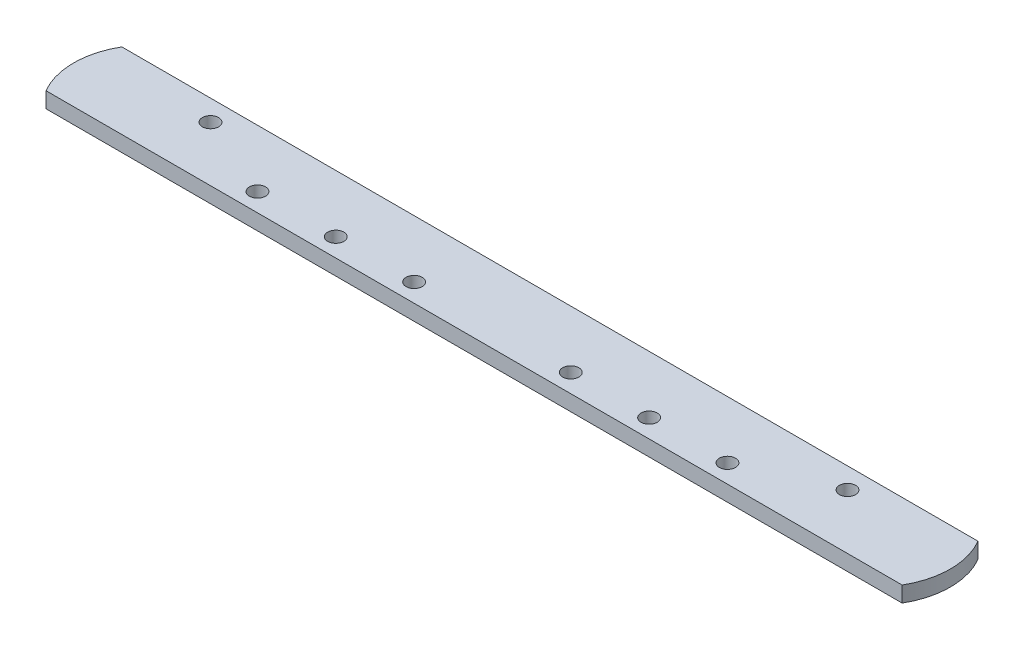
SolidWorks part; units mm, degrees
ref_plane "前视基准面" through (0, 0, 0) normal (0, 0, 1) x (1, 0, 0)
ref_plane "上视基准面" through (0, 0, 0) normal (0, 1, 0) x (1, 0, 0)
ref_plane "右视基准面" through (0, 0, 0) normal (1, 0, 0) x (0, 0, -1)
other "Configuration Table"
sketch "草图2" plane through (0, 0, 0) normal (0, 1, 0) x (1, 0, 0)
  line L0 (-82.2482, 7.3997) -> (81.7125, 7.3997)
  line L1 (-0.2678, 7.3997) -> (-0.2678, -7.1318) construction
  line L2 (81.7125, -7.1318) -> (-82.2482, -7.1318)
  arc A0 (-82.2482, 7.3997) -> (-82.2482, -7.1318) centre (-69.8675, 0.1339) ccw
  arc A1 (81.7125, 7.3997) -> (81.7125, -7.1318) centre (69.3318, 0.1339) cw
  circle A2 centre (-61.2775, 3.3997) radius 1.55
  circle A3 centre (-15.2775, -3.6003) radius 1.55
  circle A4 centre (14.7225, -3.6003) radius 1.55
  circle A5 centre (60.7225, 3.3997) radius 1.55
  circle A6 centre (-45.2775, -3.6003) radius 1.55
  circle A7 centre (-30.2775, -3.6003) radius 1.55
  circle A8 centre (29.7225, -3.6003) radius 1.55
  circle A9 centre (44.7225, -3.6003) radius 1.55
extrude "凸台-拉伸2" add sketch "草图2" along normal blind 3
